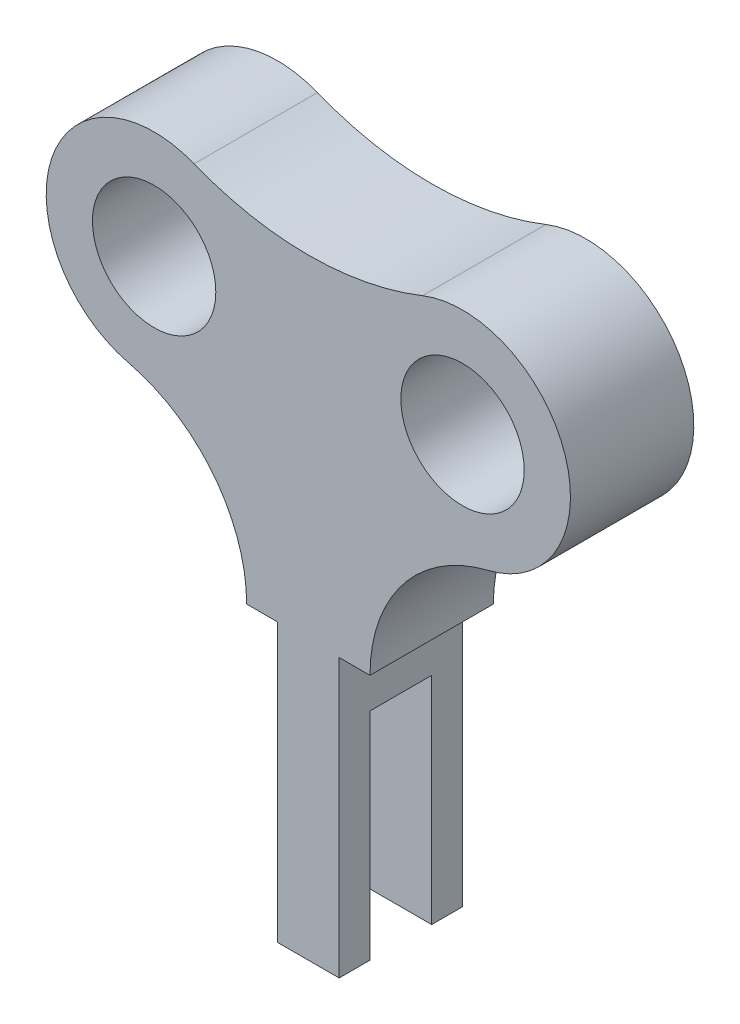
SolidWorks part; units mm, degrees
ref_plane "Front Plane" through (0, 0, 0) normal (0, 0, 1) x (1, 0, 0)
ref_plane "Top Plane" through (0, 0, 0) normal (0, 1, 0) x (1, 0, 0)
ref_plane "Right Plane" through (0, 0, 0) normal (1, 0, 0) x (0, 0, -1)
sketch "Sketch1" plane through (0, 0, 0) normal (0, 0, 1) x (1, 0, 0)
  line L0 (-39.8204, 0) -> (54.9177, 0) construction
  line L1 (-60.3817, -41.3068) -> (0.2288, -41.3068) construction
  line L2 (-4.7712, -41.3068) -> (0.2288, -41.3068)
  line L3 (10.2288, -41.3068) -> (77.1864, -41.3068) construction
  line L5 (0.2288, -41.3068) -> (0.2288, -86.3068)
  line L6 (0.2288, -86.3068) -> (10.2288, -86.3068)
  line L7 (10.2288, -41.3068) -> (10.2288, -86.3068)
  line L8 (10.2288, -41.3068) -> (15.2288, -41.3068)
  circle A0 centre (-19.7712, 0) radius 10
  circle A1 centre (30.2288, 0) radius 10
  arc A2 (-13.2897, 16.2555) -> (-23.8888, -17.0087) centre (-19.7712, 0) ccw
  arc A3 (34.3465, -17.0087) -> (23.7473, 16.2555) centre (30.2288, 0) ccw
  arc A4 (-13.2897, 16.2555) -> (23.7473, 16.2555) centre (5.2288, 62.6997) ccw
  arc A5 (-4.7712, -41.3068) -> (-23.8888, -17.0087) centre (-29.7712, -41.3068) ccw
  arc A6 (34.3465, -17.0087) -> (15.2288, -41.3068) centre (40.2288, -41.3068) ccw
  dimension "D1" = 20
  dimension "D2" = 35
  dimension "D3" = 20
  dimension "D4" = 35
  dimension "D6" = 50
  dimension "D7" = 50
  dimension "D5" = 50
  dimension "D8" = 70
  dimension "D9" = 10
  dimension "D10" = 45
  dimension "D11" = 5
  dimension "D12" = 5
extrude "Boss-Extrude1" add sketch "Sketch1" along normal blind 20
sketch "Sketch2" plane through (10.2288, 0, 0) normal (1, 0, 0) x (0, 0, -1)
  line L0 (-20, -86.3068) -> (0, -86.3068) construction
  line L1 (-15, -86.3068) -> (-5, -86.3068)
  line L2 (-15, -86.3068) -> (-15, -51.3068)
  line L3 (-15, -51.3068) -> (-5, -51.3068)
  line L4 (-5, -86.3068) -> (-5, -51.3068)
  line L5 (-20, -86.3068) -> (-20, -41.3068) construction
  dimension "D1" = 10
  dimension "D2" = 35
  dimension "D3" = 5
extrude "Cut-Extrude1" cut sketch "Sketch2" against normal blind 20
